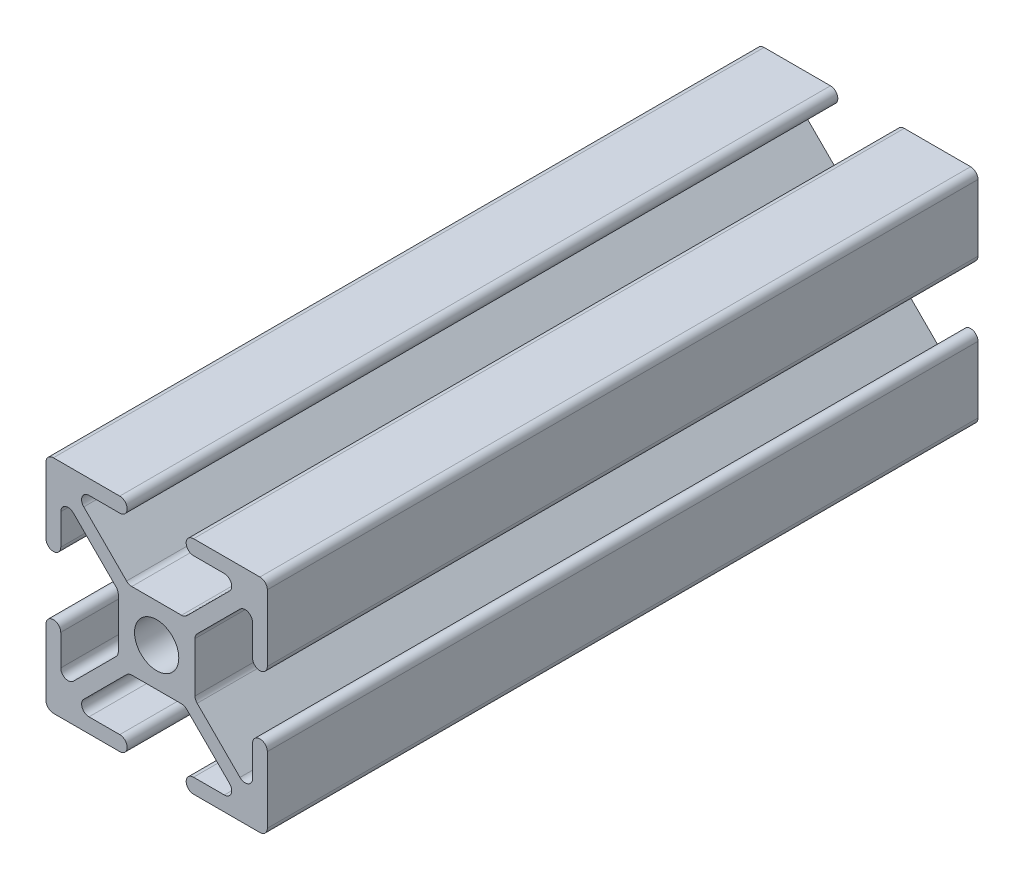
SolidWorks part; units mm, degrees
ref_plane "Alzado" through (0, 0, 0) normal (0, 0, 1) x (1, 0, 0)
ref_plane "Planta" through (0, 0, 0) normal (0, 1, 0) x (1, 0, 0)
ref_plane "Vista lateral" through (0, 0, 0) normal (1, 0, 0) x (0, 0, -1)
sketch "Croquis1" plane through (0, 0, 0) normal (0, 0, 1) x (1, 0, 0)
  line L1 (-14, 15) -> (14, 15)
  line L2 (-15, 14) -> (-15, -14)
  line L3 (-14, -15) -> (14, -15)
  line L4 (15, 14) -> (15, -14)
  line L5 (-15, 15) -> (15, -15) construction
  line L6 (-15, -15) -> (15, 15) construction
  arc A0 (-14, 15) -> (-15, 14) centre (-14, 14) ccw
  arc A1 (14, -15) -> (15, -14) centre (14, -14) ccw
  arc A2 (-14, -15) -> (-15, -14) centre (-14, -14) cw
  arc A3 (15, 14) -> (14, 15) centre (14, 14) ccw
  point P0 (0, 0)
  dimension "D3" = 1
  dimension "D4" = 1
  dimension "D1" = 30
  dimension "D2" = 30
extrude "Saliente-Extruir1" add sketch "Croquis1" against normal blind 96.34
sketch "Croquis2" plane through (0, 0, 0) normal (0, 0, 1) x (1, 0, 0)
  circle A0 centre (0, 0) radius 3
  dimension "D1" = 6
sketch "Croquis3" plane through (0, 0, 0) normal (0, 0, 1) x (1, 0, 0)
  line L0 (-15, 0) -> (15, 0) construction
  line L1 (4.0787, -5.4929) -> (9.8787, -11.2929)
  line L2 (-11.2929, 9.8787) -> (-5.4929, 4.0787)
  line L3 (-9.8787, 11.2929) -> (-4.0787, 5.4929)
  line L4 (-13, 9.1716) -> (-13, 5)
  line L5 (-15, 14) -> (-15, -14) construction
  line L6 (-5.2, 3.3716) -> (-5.2, -3.3716)
  line L7 (-9.1716, 13) -> (-5, 13)
  line L8 (9.8787, 11.2929) -> (4.0787, 5.4929)
  line L9 (11.2929, 9.8787) -> (5.4929, 4.0787)
  line L10 (-3.3716, 5.2) -> (3.3716, 5.2)
  line L11 (14, 15) -> (-14, 15) construction
  line L12 (13, 9.1716) -> (13, 5)
  line L13 (5.2, 3.3716) -> (5.2, -3.3716)
  line L14 (15, -14) -> (15, 14) construction
  line L15 (-9.1716, -13) -> (-5, -13)
  line L16 (-3.3716, -5.2) -> (3.3716, -5.2)
  line L17 (-14, -15) -> (14, -15) construction
  line L18 (-5.4929, -4.0787) -> (-11.2929, -9.8787)
  line L19 (5.4929, -4.0787) -> (11.2929, -9.8787)
  line L20 (-4.0787, -5.4929) -> (-9.8787, -11.2929)
  line L21 (5, -13) -> (9.1716, -13)
  line L22 (-13, -5) -> (-13, -9.1716)
  line L23 (13, -5) -> (13, -9.1716)
  line L24 (0, 15) -> (0, -5.2) construction
  line L34 (5, 13) -> (9.1716, 13)
  arc A0 (9.8787, 11.2929) -> (9.1716, 13) centre (9.1716, 12) ccw
  arc A1 (-9.8787, 11.2929) -> (-9.1716, 13) centre (-9.1716, 12) cw
  arc A2 (9.8787, 11.2929) -> (9.1716, 13) centre (9.1716, 12) ccw
  arc A3 (13, 9.1716) -> (11.2929, 9.8787) centre (12, 9.1716) ccw
  arc A4 (11.2929, -9.8787) -> (13, -9.1716) centre (12, -9.1716) ccw
  arc A5 (9.1716, -13) -> (9.8787, -11.2929) centre (9.1716, -12) ccw
  arc A6 (-9.1716, -13) -> (-9.8787, -11.2929) centre (-9.1716, -12) cw
  arc A7 (-11.2929, -9.8787) -> (-13, -9.1716) centre (-12, -9.1716) cw
  arc A8 (-13, 9.1716) -> (-11.2929, 9.8787) centre (-12, 9.1716) cw
  arc A9 (-4.0787, -5.4929) -> (-3.3716, -5.2) centre (-3.3716, -6.2) cw
  arc A10 (3.3716, -5.2) -> (4.0787, -5.4929) centre (3.3716, -6.2) cw
  arc A11 (5.4929, -4.0787) -> (5.2, -3.3716) centre (6.2, -3.3716) cw
  arc A12 (5.2, 3.3716) -> (5.4929, 4.0787) centre (6.2, 3.3716) cw
  arc A13 (3.3716, 5.2) -> (4.0787, 5.4929) centre (3.3716, 6.2) ccw
  arc A14 (-3.3716, 5.2) -> (-4.0787, 5.4929) centre (-3.3716, 6.2) cw
  arc A15 (-5.4929, -4.0787) -> (-5.2, -3.3716) centre (-6.2, -3.3716) ccw
  arc A16 (-5.2, 3.3716) -> (-5.4929, 4.0787) centre (-6.2, 3.3716) ccw
  circle A17 centre (-14, -5) radius 1
  circle A18 centre (-14, 5) radius 1
  circle A19 centre (-5, -14) radius 1
  circle A20 centre (5, -14) radius 1
  circle A21 centre (14, 5) radius 1
  circle A22 centre (14, -5) radius 1
  circle A23 centre (-5, 14) radius 1
  circle A24 centre (5, 14) radius 1
  point P20 (-11.5858, -13)
  point P30 (-13, -11.5858)
  point P43 (-3.7858, -5.2)
  point P50 (3.7858, -5.2)
  point P53 (5.2, -3.7858)
  point P62 (-5.2, -3.7858)
  line M2 (-15, 14) -> (-15, -14)
  line M4 (-14, -15) -> (14, -15)
  line M6 (15, -14) -> (15, 14)
  line M8 (14, 15) -> (-14, 15)
  dimension "D6" = 9.8
  dimension "D7" = 2
  dimension "D12" = 2
  dimension "D19" = 1
  dimension "D2" = 1
  dimension "D3" = 1
  dimension "D4" = 1
  dimension "D16" = 1
  dimension "D5" = 2
  dimension "D8" = 9.8
  dimension "D9" = 2
  dimension "D10" = 9.8
  dimension "D11" = 9.8
  dimension "D15" = 1
  dimension "D20" = 1
  dimension "D23" = 1
  dimension "D24" = 1
  dimension "D27" = 1
  dimension "D28" = 1
extrude "Cortar-Extruir1" cut sketch "Croquis2" against normal through all
extrude "Cortar-Extruir3" cut sketch "Croquis3" against normal through all contours A18 A17 L22 A7 L18 A15 L6 A16 L2 A8 L4 M2 | A24 A23 L7 A1 L3 A14 L10 A13 L8 A0 L34 M8 | A20 L21 A5 L1 A10 L16 A9 L20 A6 L15 A19 M4 | A22 A21 L12 A3 L9 A12 L13 A11 L19 A4 L23 M6
